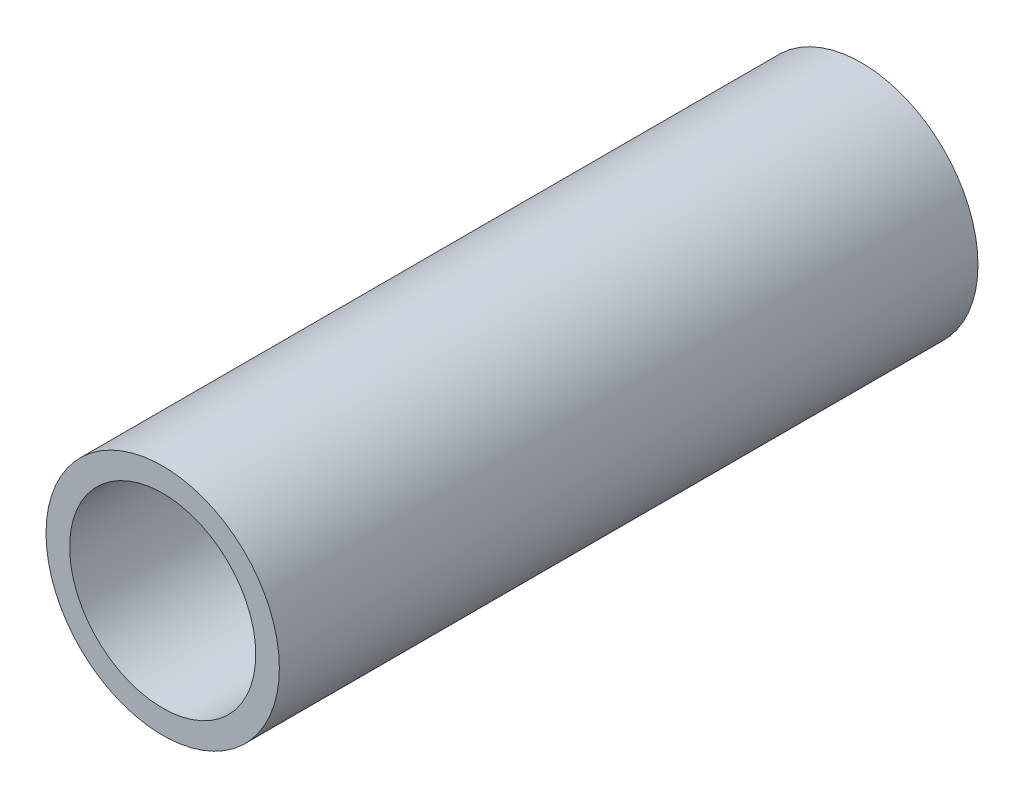
SolidWorks part; units mm, degrees
ref_plane "Front Plane" through (0, 0, 0) normal (0, 0, 1) x (1, 0, 0)
ref_plane "Top Plane" through (0, 0, 0) normal (0, 1, 0) x (1, 0, 0)
ref_plane "Right Plane" through (0, 0, 0) normal (1, 0, 0) x (0, 0, -1)
sketch "Sketch1" plane through (0, 0, 0) normal (0, 0, 1) x (1, 0, 0)
  circle A0 centre (0, 0) radius 16.7005
  dimension "Pipe OD" = 33.401
extrude "Extrude-Thin1" add sketch "Sketch1" along normal mid plane 100 thin thin type one direction reverse wall 3.3782
